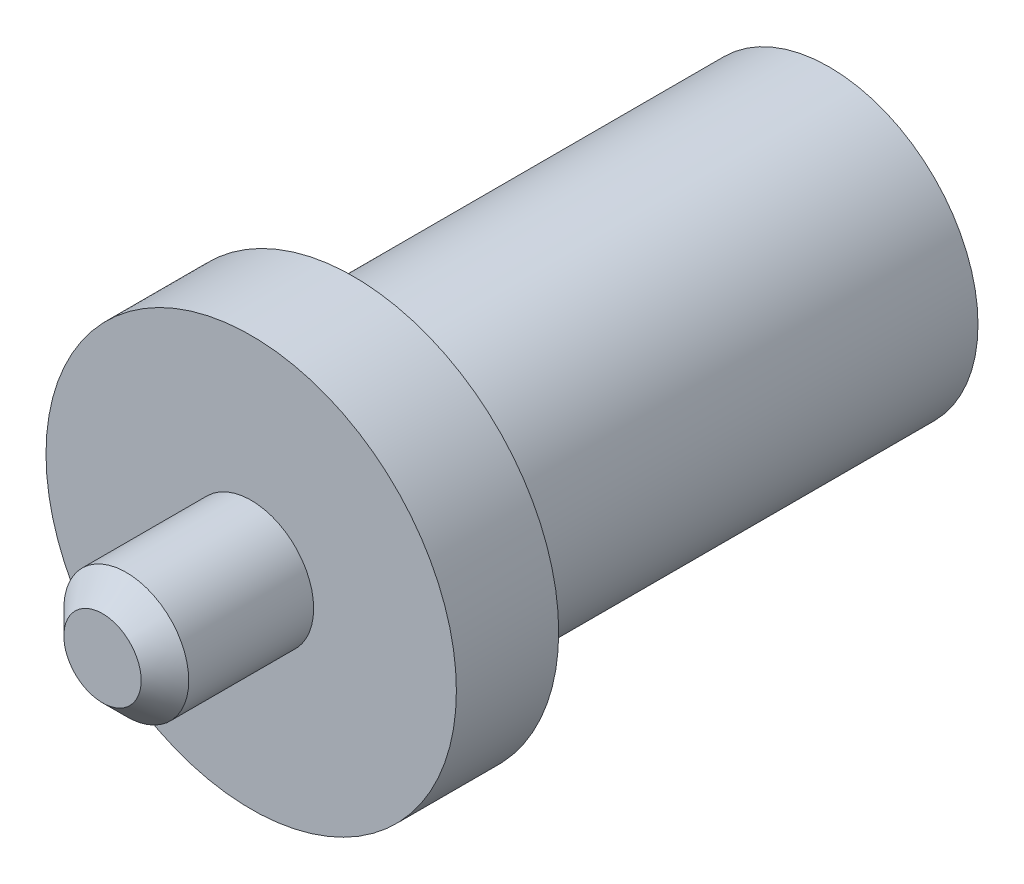
SolidWorks part; units mm, degrees
ref_plane "Front Plane" through (0, 0, 0) normal (0, 0, 1) x (1, 0, 0)
ref_plane "Top Plane" through (0, 0, 0) normal (0, 1, 0) x (1, 0, 0)
ref_plane "Right Plane" through (0, 0, 0) normal (1, 0, 0) x (0, 0, -1)
sketch "Sketch1" plane through (0, 0, 0) normal (0, 0, 1) x (1, 0, 0)
  circle A0 centre (0, 0) radius 3.45
  dimension "D1" = 6.9
extrude "Boss-Extrude1" add sketch "Sketch1" against normal blind 1.72
sketch "Sketch2" plane through (0, 0, -1.72) normal (0, 0, -1) x (-1, 0, 0)
  circle A0 centre (0, 0) radius 2.5
extrude "Boss-Extrude2" add sketch "Sketch2" along normal blind 8
sketch "Sketch3" plane through (0, 0, 0) normal (0, 0, 1) x (1, 0, 0)
  circle A0 centre (0, 0) radius 1.05
extrude "Boss-Extrude3" add sketch "Sketch3" along normal blind 2.5
chamfer "Chamfer1" distance 0.4 angle 45 1 edges at (1.05, 0, 2.5)
